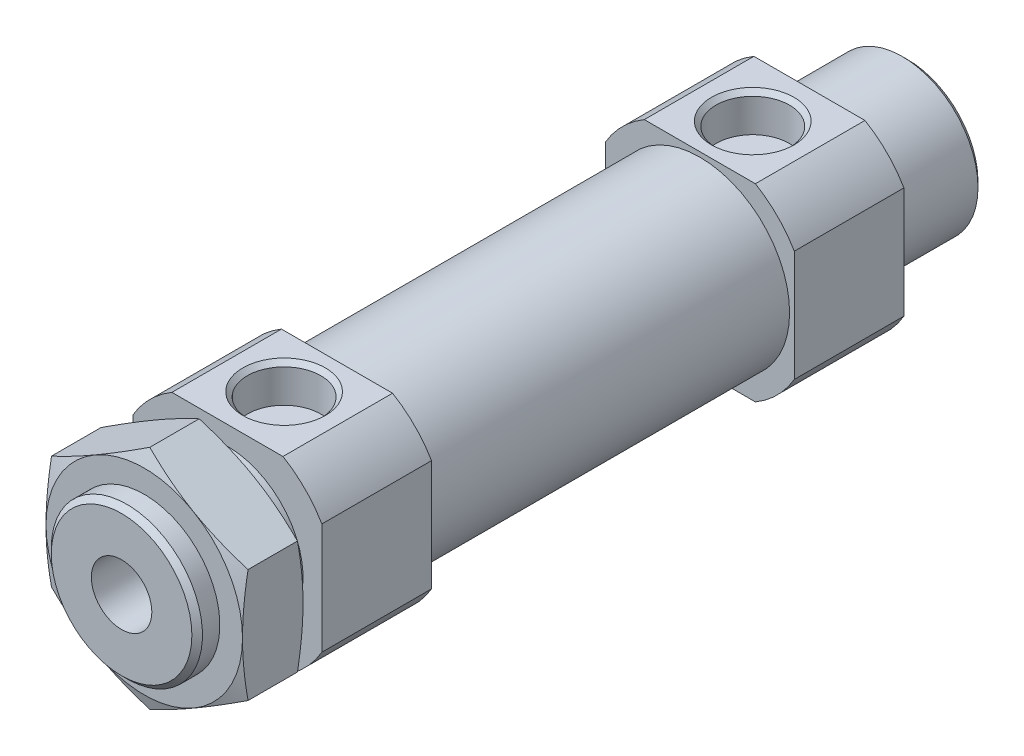
SolidWorks part; units mm, degrees
ref_plane "前视基准面" through (0, 0, 0) normal (0, 0, 1) x (1, 0, 0)
ref_plane "上视基准面" through (0, 0, 0) normal (0, 1, 0) x (1, 0, 0)
ref_plane "右视基准面" through (0, 0, 0) normal (1, 0, 0) x (0, 0, -1)
sketch "草图1" plane through (0, 0, 0) normal (1, 0, 0) x (0, 0, -1)
  line L0 (-38.5, 0) -> (38.5, 0) construction
  line L1 (0, 0) -> (0, 12.5) construction
  line L2 (0, 12.5) -> (15, 12.5) construction
  line L3 (15, 12.5) -> (77, 12.5) construction
  line L4 (51.5, 10) -> (51.5, -10) construction
  line L5 (-38.5, 0) -> (-52.5, 0) construction
  line L6 (-52.5, 10) -> (-52.5, -10) construction
  line L7 (-52.5, 0) -> (-79.5, 0) construction
  line L8 (38.5, 0) -> (59.5, 0) construction
  line L9 (59.5, 10) -> (59.5, -10) construction
  line L10 (-79.5, 4) -> (-79.5, -4) construction
  line L11 (38.5, 0) -> (24, 0)
  circle A0 centre (-31, 0) radius 4.864
  circle A1 centre (50.5, 0) radius 4
  point P6 (-24, 0)
  point P8 (24, 0)
  point P9 (-31, 0)
  point P10 (31, 0)
  point P13 (51.5, 0)
  point P16 (-49.5, 0)
  point P18 (-41.5, 0)
  point P21 (-52.5, 4)
  point P22 (-64, 0)
  point P24 (-62.05, 0)
  point P25 (-57.05, 0)
  point P26 (-74.85, 0)
  point P27 (-69.85, 0)
  point P28 (50.5, 0)
  point P36 (31, 0)
  dimension "X" = 9.728
  dimension "P1" = 8
  dimension "D1" = 77
  dimension "行程" = 15
  dimension "A" = 62
  dimension "S" = 25
  dimension "F" = 14.5
  dimension "G1" = 7.5
  dimension "D1用" = 13
  dimension "L" = 20
  dimension "B" = 14
  dimension "M" = 8
  dimension "D3" = 1.95
  dimension "V" = 8
  dimension "C" = 27
  dimension "H" = 15.5
  dimension "D4" = 4.65
  dimension "E" = 5
  dimension "J" = 5
  dimension "D" = 21
  dimension "G" = 12
  dimension "L1" = 20
  dimension "K" = 8
  dimension "固定厚度" = 3
  dimension "F1" = 14.5
  dimension "G2" = 7.5
sketch "草图2" plane through (0, 0, 0) normal (0, 0, 1) x (1, 0, 0)
  line L0 (-6, 0) -> (6, 0) construction
  line L1 (0, 15.0111) -> (-13, 7.5056)
  line L2 (-13, 7.5056) -> (-13, -7.5056)
  line L3 (-13, -7.5056) -> (0, -15.0111)
  line L4 (0, -15.0111) -> (13, -7.5056)
  line L5 (13, -7.5056) -> (13, 7.5056)
  line L6 (13, 7.5056) -> (0, 15.0111)
  line L7 (0, 7.5056) -> (-6.5, 3.7528)
  line L8 (-6.5, 3.7528) -> (-6.5, -3.7528)
  line L9 (-6.5, -3.7528) -> (0, -7.5056)
  line L10 (0, -7.5056) -> (6.5, -3.7528)
  line L11 (6.5, -3.7528) -> (6.5, 3.7528)
  line L12 (6.5, 3.7528) -> (0, 7.5056)
  line L13 (0, 0) -> (0, 4) construction
  circle A0 centre (0, 0) radius 13 construction
  circle A1 centre (0, 0) radius 6.5 construction
  circle A2 centre (0, 0) radius 14.5 construction
  dimension "T1" = 26
  dimension "T" = 13
  dimension "P" = 29
  dimension "Q" = 12
sketch "行程" plane through (0, 0, 0) normal (1, 0, 0) x (0, 0, -1)
  line L0 (24, 0) -> (9, 0)
  line L1 (-38.5, 0) -> (38.5, 0) construction
  line L2 (9, 0) -> (9, 1)
  line L3 (24, 0) -> (24, 1)
  dimension "D1" = 15
  dimension "D2" = 1
sketch "草图4" plane through (0, 0, 0) normal (0, 0, 1) x (1, 0, 0)
  line L1 (-12.5, -12.5) -> (12.5, -12.5)
  line L2 (-12.5, -12.5) -> (-12.5, 12.5)
  line L3 (-12.5, 12.5) -> (12.5, 12.5)
  line L4 (12.5, -12.5) -> (12.5, 12.5)
  line L5 (-12.5, -12.5) -> (12.5, 12.5) construction
  line L6 (-12.5, 12.5) -> (12.5, -12.5) construction
  point P0 (0, 0)
extrude "凸台-拉伸1" add sketch "草图4" against normal up to vertex (-24 mm away) from vertex at 38.5 starting at point (0, 0, 38.5)
sketch "草图5" plane through (0, 0, 24) normal (0, 0, -1) x (-1, 0, 0)
  circle A0 centre (0, 0) radius 11.875
  dimension "D1" = 23.75
extrude "凸台-拉伸2" add sketch "草图5" along normal up to vertex (62.5 mm away) up to point (0, 0, -38.5)
mirror "镜向1" about plane through (0, 0, 0) normal (0, 0, 1) of "凸台-拉伸1"
sketch "草图6" plane through (0, 0, 38.5) normal (0, 0, 1) x (1, 0, 0)
  circle A0 centre (0, 0) radius 10
extrude "凸台-拉伸3" add sketch "草图6" along normal up to vertex (14 mm away) up to point (0, 0, 52.5)
cosmetic thread "装饰螺纹线1" parameters "D2"=17
cosmetic thread "装饰螺纹线2" parameters "D2"=17
cosmetic thread "装饰螺纹线9" [suppressed] parameters "D2"=17
sketch "草图7" plane through (0, 0, 0) normal (0, 0, 1) x (1, 0, 0)
  line L0 (13, 7.5056) -> (0, 15.0111) construction
  line L1 (0, 15.0111) -> (-13, 7.5056) construction
  line L2 (-13, 7.5056) -> (-13, -7.5056) construction
  line L3 (-13, -7.5056) -> (0, -15.0111) construction
  line L4 (0, -15.0111) -> (13, -7.5056) construction
  line L5 (13, -7.5056) -> (13, 7.5056) construction
  line L6 (13, 7.5056) -> (0, 15.0111)
  line L7 (0, 15.0111) -> (-13, 7.5056)
  line L8 (-13, 7.5056) -> (-13, -7.5056)
  line L9 (-13, -7.5056) -> (0, -15.0111)
  line L10 (0, -15.0111) -> (13, -7.5056)
  line L11 (13, -7.5056) -> (13, 7.5056)
extrude "凸台-拉伸4" add sketch "草图7" against normal up to vertex (-41.5 mm away) from vertex at 49.5 starting at point (0, 0, 49.5)
sketch "草图10" plane through (0, 0, 0) normal (0, 1, 0) x (1, 0, 0)
  line L0 (-13, -45.5) -> (0, -45.5) construction
  line L1 (-13, -41.5) -> (-13, -49.5) construction
  line L2 (0, -38.5) -> (0, -52.5) construction
  line L3 (-13, -49.5) -> (-25.9899, -49.5)
  line L4 (-13, -49.5) -> (-23.9899, -45.5)
  line L5 (-13, -41.5) -> (-23.9899, -45.5)
  line L6 (-13, -41.5) -> (-25.9899, -41.5)
  line L7 (-25.9899, -41.5) -> (-25.9899, -49.5)
  dimension "D1" = 20
  dimension "D2" = 2
revolve "切除-旋转1" cut sketch "草图10" angle 360 mid plane about L7
sketch "草图8" plane through (0, 12.5, 0) normal (0, 1, 0) x (1, 0, 0)
  circle A0 centre (0, -31) radius 4.864
  dimension "D1" = 9.728
extrude "切除-拉伸1" cut sketch "草图8" against normal up to vertex (4.9944 mm away) up to point (0, 7.5056, 0)
cosmetic thread "装饰螺纹线3" parameters "D2"=9.828
mirror "镜向2" about plane through (0, 0, 0) normal (0, 0, 1) of "切除-拉伸1"
sketch "草图9" plane through (0, 0, 38.5) normal (0, 0, 1) x (1, 0, 0)
  circle A0 centre (0, 0) radius 14.5 construction
  circle A1 centre (0, 0) radius 14.5
extrude "切除-拉伸2" cut sketch "草图9" against normal up to surface (77 mm away) flip side to cut up to face at (0, 0, -38.5)
sketch "草图11" plane through (0, 0, 52.5) normal (0, 0, 1) x (1, 0, 0)
  circle A0 centre (0, 0) radius 4
extrude "切除-拉伸3" cut sketch "草图11" against normal up to vertex (76.5 mm away) up to point (0, 0, -24)
chamfer "倒角1" distance 0.7 angle 45 1 edges at (10, 0, 52.5)
chamfer "倒角2" distance 0.5973 angle 45 2 edges at (0, 12.5, -35.864) (0, 12.5, 35.864)
sketch "草图18" [suppressed] plane through (0, 0, -36) normal (0, 0, -1) x (-1, 0, 0)
  line L4 (12.5, -7.3485) -> (12.5, 7.3485)
  line L5 (7.3485, 12.5) -> (-7.3485, 12.5)
  line L6 (-12.5, 7.3485) -> (-12.5, -7.3485)
  line L7 (-7.3485, -12.5) -> (7.3485, -12.5)
  line L8 (12.5, -7.3485) -> (12.5, 7.3485)
  line L9 (7.3485, 12.5) -> (-7.3485, 12.5)
  line L10 (-12.5, 7.3485) -> (-12.5, -7.3485)
  line L11 (-7.3485, -12.5) -> (7.3485, -12.5)
  arc A4 (12.5, 7.3485) -> (7.3485, 12.5) centre (0, 0) ccw
  arc A5 (-7.3485, 12.5) -> (-12.5, 7.3485) centre (0, 0) ccw
  arc A6 (-12.5, -7.3485) -> (-7.3485, -12.5) centre (0, 0) ccw
  arc A7 (7.3485, -12.5) -> (12.5, -7.3485) centre (0, 0) ccw
  arc A8 (12.5, 7.3485) -> (7.3485, 12.5) centre (0, 0) ccw
  arc A9 (-7.3485, 12.5) -> (-12.5, 7.3485) centre (0, 0) ccw
  arc A10 (-12.5, -7.3485) -> (-7.3485, -12.5) centre (0, 0) ccw
  arc A11 (7.3485, -12.5) -> (12.5, -7.3485) centre (0, 0) ccw
  dimension "D1" = 0
extrude "凸台-拉伸7" [suppressed] add sketch "草图18" against normal up to vertex
sketch "草图19" [suppressed] plane through (0, 12.5, 0) normal (0, 1, 0) x (1, 0, 0)
  line L0 (0, 36) -> (0, 21.5) construction
  circle A0 centre (0, 28.5) radius 4.864
  dimension "D1" = 9.728
extrude "切除-拉伸10" [suppressed] cut sketch "草图19" against normal up to surface (4.9944 mm away)
cosmetic thread "装饰螺纹线7" [suppressed] parameters "D2"=9.828
cosmetic thread "装饰螺纹线8" [suppressed] parameters "D2"=9.828
chamfer "倒角5" [suppressed] distance 0.5973 angle 45
sketch "草图12" plane through (0, 0, -38.5) normal (0, 0, -1) x (-1, 0, 0)
  circle A0 centre (0, 0) radius 10
extrude "凸台-拉伸5" add sketch "草图12" along normal up to vertex (13 mm away) up to point (0, 0, -51.5)
cosmetic thread "装饰螺纹线4" parameters "D2"=17
sketch "草图13" plane through (0, 0, -38.5) normal (0, 0, -1) x (-1, 0, 0)
  circle A0 centre (0, 0) radius 9
  circle A1 centre (0, 0) radius 10 construction
  circle A2 centre (0, 0) radius 10
  dimension "D1" = 18
extrude "切除-拉伸4" cut sketch "草图13" along normal blind 1.3
chamfer "倒角3" distance 0.7 angle 45 1 edges at (-10, 0, -51.5)
sketch "草图14" [suppressed] plane through (0, 0, -36) normal (0, 0, -1) x (-1, 0, 0)
  circle A0 centre (0, 0) radius 10
extrude "凸台-拉伸6" [suppressed] add sketch "草图14" along normal up to vertex
cosmetic thread "装饰螺纹线5" [suppressed] parameters "D2"=17
cosmetic thread "装饰螺纹线6" [suppressed] parameters "D2"=17
sketch "草图15" [suppressed] plane through (0, 0, -36) normal (0, 0, -1) x (-1, 0, 0)
  circle A0 centre (0, 0) radius 9
  circle A1 centre (0, 0) radius 10 construction
  circle A2 centre (0, 0) radius 10
  dimension "D1" = 18
extrude "切除-拉伸7" [suppressed] cut sketch "草图15" along normal blind 1.05
chamfer "倒角4" [suppressed] distance 0.7 angle 45
sketch "草图16" [suppressed] plane through (0, 0, -57) normal (0, 0, -1) x (-1, 0, 0)
  line L0 (-6, 10) -> (-6, -10)
  line L1 (6, 10) -> (6, -10)
  line L2 (-6, 10) -> (6, 10)
  line L3 (-6, -10) -> (6, -10)
  circle A0 centre (0, 0) radius 10 construction
extrude "切除-拉伸8" [suppressed] cut sketch "草图16" against normal up to surface (21 mm away) flip side to cut
sketch "草图17" [suppressed] plane through (6, 0, 0) normal (1, 0, 0) x (0, 0, -1)
  circle A0 centre (48, 0) radius 4 construction
  circle A1 centre (48, 0) radius 4
extrude "切除-拉伸9" [suppressed] cut sketch "草图17" against normal through all
